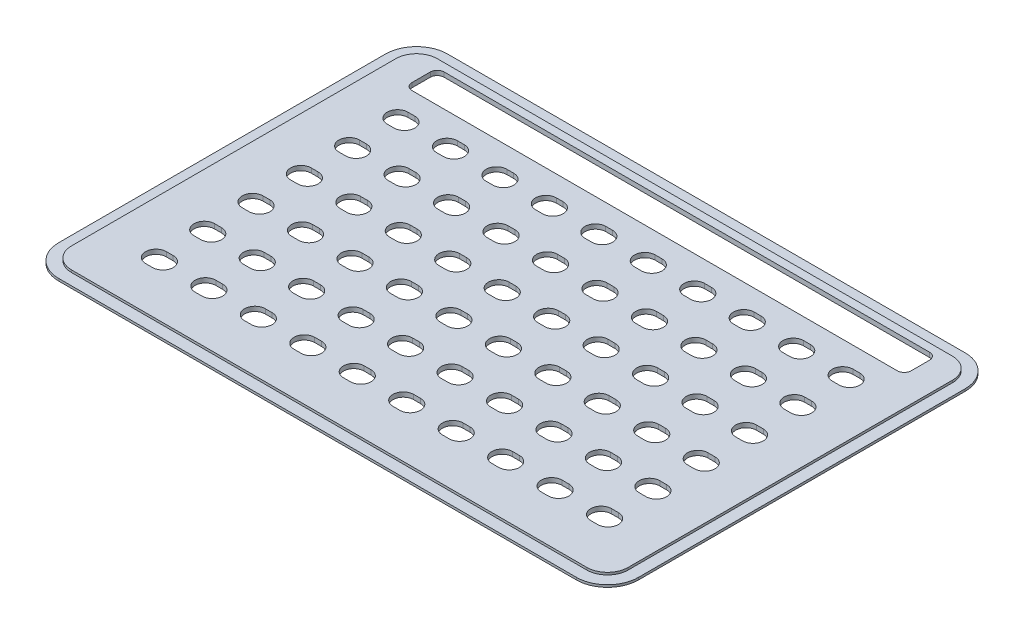
SolidWorks part; units mm, degrees
ref_plane "Front Plane" through (0, 0, 0) normal (0, 0, 1) x (1, 0, 0)
ref_plane "Top Plane" through (0, 0, 0) normal (0, 1, 0) x (1, 0, 0)
ref_plane "Right Plane" through (0, 0, 0) normal (1, 0, 0) x (0, 0, -1)
sketch "Sketch1" plane through (0, 0, 0) normal (0, 1, 0) x (1, 0, 0)
  line L1 (-126, -84.5) -> (126, -84.5)
  line L2 (-126, -84.5) -> (-126, 84.5)
  line L3 (-126, 84.5) -> (126, 84.5)
  line L4 (126, -84.5) -> (126, 84.5)
  line L5 (-126, -84.5) -> (126, 84.5) construction
  line L6 (-126, 84.5) -> (126, -84.5) construction
  point P0 (0, 0)
  dimension "D1" = 252
  dimension "D2" = 169
extrude "Outer Profile" add sketch "Sketch1" along normal blind 1
sketch "Sketch2" plane through (0, 1, 0) normal (0, 1, 0) x (1, 0, 0)
  line L0 (-126, 84.5) -> (-126, -84.5) construction
  line L1 (-121, -79.5) -> (121, -79.5)
  line L2 (-121, -79.5) -> (-121, 79.5)
  line L3 (-121, 79.5) -> (121, 79.5)
  line L4 (121, -79.5) -> (121, 79.5)
  line L5 (-121, -79.5) -> (121, 79.5) construction
  line L6 (-121, 79.5) -> (121, -79.5) construction
  line L7 (126, 84.5) -> (-126, 84.5) construction
  point P0 (0, 0)
  dimension "D1" = 5
  dimension "D2" = 5
extrude "Inner Profile" add sketch "Sketch2" along normal blind 1
fillet "Fillet1" radius 9 4 edges at (121, 1.5, 79.5) (121, 1.5, -79.5) (-121, 1.5, -79.5) (-121, 1.5, 79.5)
fillet "Fillet2" radius 13.5 4 edges at (-126, 0.5, -84.5) (126, 0.5, -84.5) (126, 0.5, 84.5) (-126, 0.5, 84.5)
sketch "Sketch3" plane through (0, 2, 0) normal (0, 1, 0) x (1, 0, 0)
  line L0 (0, 0) -> (0, -50000) construction
  line L1 (-109.5, -68.5) -> (109.5, -68.5) construction
  line L2 (-109.5, -68.5) -> (-109.5, 68.5) construction
  line L3 (-109.5, 68.5) -> (109.5, 68.5) construction
  line L4 (109.5, -68.5) -> (109.5, 68.5) construction
  line L5 (-109.5, -68.5) -> (109.5, 68.5) construction
  line L6 (-109.5, 68.5) -> (109.5, -68.5) construction
  line L7 (-12.25, -56.5) -> (-9.25, -56.5) construction
  line L8 (-12.25, -52) -> (-9.25, -52)
  line L9 (-12.25, -61) -> (-9.25, -61)
  arc A0 (-12.25, -52) -> (-12.25, -61) centre (-12.25, -56.5) ccw
  arc A1 (-9.25, -61) -> (-9.25, -52) centre (-9.25, -56.5) ccw
  point P0 (0, 0)
  point P5 (-10.75, -56.5)
  point P9 (-10.75, -56.5)
  dimension "D6" = 12
  dimension "D1" = 219
  dimension "D2" = 137
  dimension "D3" = 21.5
  dimension "D4" = 12
  dimension "D5" = 9
chamfer "Chamfer" [suppressed] distance 0.5 angle 45
extrude "Cutout" cut sketch "Sketch3" against normal through all
pattern_linear "Cutouts" count 5 spacing 21.5 along (-1, 0, 0) count 6 spacing 21 along (0, 0, -1) of "Cutout"
mirror "Mirror1" about plane through (0, 0, 0) normal (1, 0, 0) of "Cutouts", "Cutout"
sketch "Sketch4" plane through (0, 2, 0) normal (0, 1, 0) x (1, 0, 0)
  line L0 (0, 79.5) -> (0, 0) construction
  line L1 (-108.5, 62) -> (108.5, 62)
  line L2 (-108.5, 62) -> (-108.5, 76)
  line L3 (-108.5, 76) -> (108.5, 76)
  line L4 (108.5, 62) -> (108.5, 76)
  line L5 (112, 79.5) -> (-112, 79.5) construction
  line L7 (-109.5, 68.5) -> (109.5, 68.5) construction
  dimension "D1" = 7.5
  dimension "D2" = 14
  dimension "D3" = 217
extrude "Message Window" cut sketch "Sketch4" against normal through all
fillet "Message Window Corners" radius 3 4 edges at (108.5, 1, -62) (-108.5, 1, -62) (108.5, 1, -76) (-108.5, 1, -76)
chamfer "Edge Chamfer" [suppressed] distance 1 angle 45
